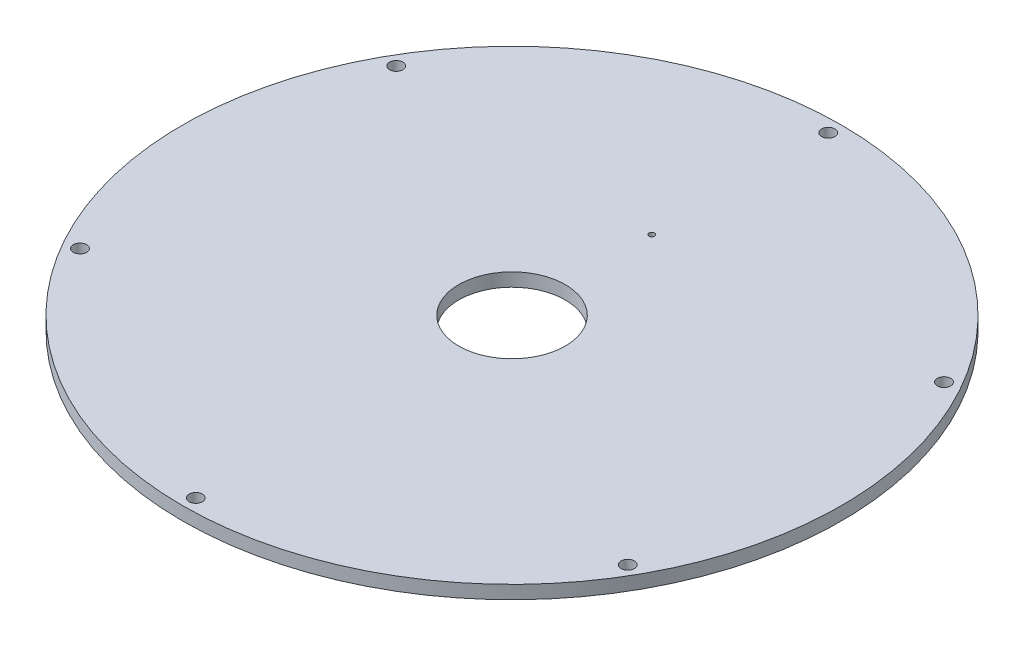
SolidWorks part; units mm, degrees
material "1060 Alloy"
ref_plane "Front Plane" through (0, 0, 0) normal (0, 0, 1) x (1, 0, 0)
ref_plane "Top Plane" through (0, 0, 0) normal (0, 1, 0) x (1, 0, 0)
ref_plane "Right Plane" through (0, 0, 0) normal (1, 0, 0) x (0, 0, -1)
sketch "Sketch1" plane through (0, 0, 0) normal (0, 1, 0) x (1, 0, 0)
  circle A0 centre (0, 0) radius 49.5
  circle A1 centre (0, 0) radius 8
  circle A2 centre (0, 47.5) radius 1
  circle A3 centre (41.1362, 23.75) radius 1
  circle A4 centre (41.1362, -23.75) radius 1
  circle A5 centre (0, -47.5) radius 1
  circle A6 centre (-41.1362, -23.75) radius 1
  circle A7 centre (-41.1362, 23.75) radius 1
  point P18 (0, 0)
  dimension "D1" = 99
  dimension "D2" = 16
  dimension "D3" = 2
  dimension "D4" = 47.5
  dimension "D5" = 6
extrude "Boss-Extrude1" add sketch "Sketch1" along normal blind 2
sketch "Sketch2" plane through (0, 2, 0) normal (0, 1, 0) x (1, 0, 0)
  circle A0 centre (0, 21) radius 0.42
  dimension "D1" = 0.84
  dimension "D2" = 21
extrude "Cut-Extrude1" cut sketch "Sketch2" against normal through all both and the other way through all
sketch "Sketch3" plane through (0, 0, 0) normal (0, -1, 0) x (1, 0, 0)
  line L0 (-6.1564, 16.9145) -> (0, 0) construction
  line L1 (0, 0) -> (-6.1564, -16.9145) construction
  line L2 (-6.1564, -16.9145) -> (0, 0) construction
  line L3 (0, 0) -> (18, 0) construction
  circle A0 centre (0, 0) radius 18
  circle A1 centre (-6.1564, 16.9145) radius 1
  circle A2 centre (-6.1564, -16.9145) radius 1
  circle A3 centre (18, 0) radius 1
  dimension "D1" = 2
  dimension "D2" = 2
  dimension "D3" = 2
  dimension "D4" = 36
  dimension "D5" = 110
  dimension "D6" = 140
extrude "Cut-Extrude2" cut sketch "Sketch3" against normal blind 1 contours A0 A2 | A0 A2 | A1 | A3
